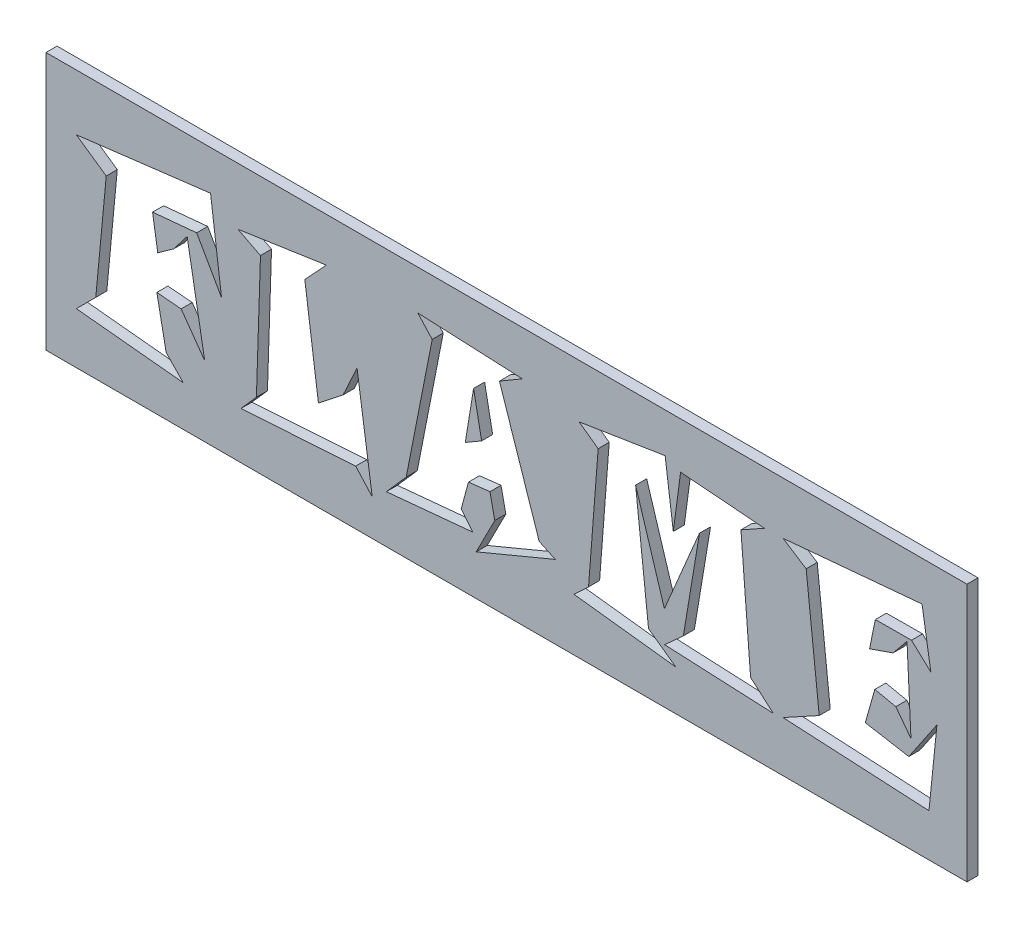
SolidWorks part; units mm, degrees
ref_plane "Front" through (0, 0, 0) normal (0, 0, 1) x (1, 0, 0)
ref_plane "Top" through (0, 0, 0) normal (0, 1, 0) x (1, 0, 0)
ref_plane "Right" through (0, 0, 0) normal (1, 0, 0) x (0, 0, -1)
sketch "Sketch1" plane through (0, 0, 0) normal (0, 0, 1) x (1, 0, 0)
  line L0 (10, 60) -> (240, 60) construction
  line L1 (0, 0) -> (250, 0) construction
  line L2 (0, 0) -> (0, 70) construction
  line L3 (0, 70) -> (250, 70) construction
  line L4 (250, 0) -> (250, 70) construction
  line L5 (240, 10) -> (240, 60) construction
  line L6 (10, 10) -> (240, 10) construction
  line L7 (10, 10) -> (10, 60) construction
  line L8 (10, 12.7542) -> (240, 12.7542) construction
  text T0 "<b>F L A M E</b>" font "Snap ITC" height in points 180
  dimension "D1" = 70
  dimension "D2" = 250
  dimension "D3" = 10
sketch "Sketch2" plane through (0, 0, 0) normal (0, 0, 1) x (1, 0, 0)
  line L1 (0, 0) -> (250, 0)
  line L2 (0, 0) -> (0, 70)
  line L3 (0, 70) -> (250, 70)
  line L4 (250, 0) -> (250, 70)
extrude "Boss-Extrude2" add sketch "Sketch2" along normal blind 3
extrude "Cut-Extrude1" cut sketch "Sketch1" along normal blind 25
